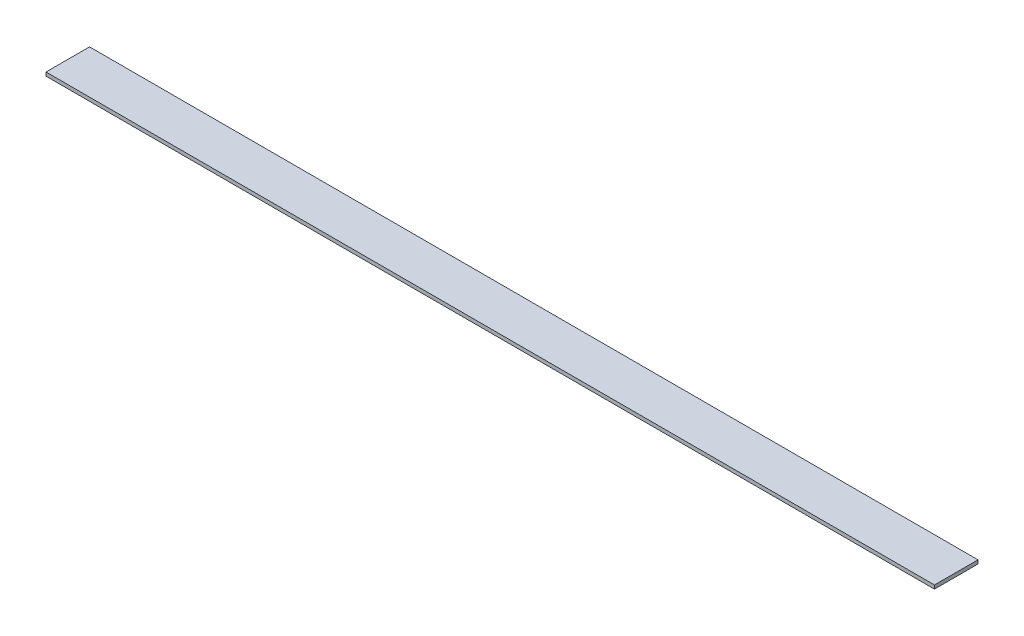
SolidWorks part; units mm, degrees
ref_plane "Front Plane" through (0, 0, 0) normal (0, 0, 1) x (1, 0, 0)
ref_plane "Top Plane" through (0, 0, 0) normal (0, 1, 0) x (1, 0, 0)
ref_plane "Right Plane" through (0, 0, 0) normal (1, 0, 0) x (0, 0, -1)
sketch "Sketch1" plane through (0, 0, 0) normal (0, 1, 0) x (1, 0, 0)
  line L1 (465, 277.5) -> (-465, 277.5)
  line L2 (465, 277.5) -> (465, -277.5)
  line L3 (465, -277.5) -> (-465, -277.5)
  line L4 (-465, 277.5) -> (-465, -277.5)
  line L5 (465, 277.5) -> (-465, -277.5) construction
  line L6 (465, -277.5) -> (-465, 277.5) construction
  line L7 (388.8, 239.4) -> (-388.8, 239.4)
  line L8 (388.8, 239.4) -> (388.8, -239.4)
  line L9 (388.8, -239.4) -> (-388.8, -239.4)
  line L10 (-388.8, 239.4) -> (-388.8, -239.4)
  line L11 (388.8, 239.4) -> (-388.8, -239.4) construction
  line L12 (388.8, -239.4) -> (-388.8, 239.4) construction
  point P0 (0, 0)
  point P6 (0, 0)
  dimension "D1" = 76.2
  dimension "D2" = 555
  dimension "D3" = 38.1
  dimension "D4" = 930
extrude "Boss-Extrude2" add sketch "Sketch1" along normal blind 3.175
sketch "Sketch2" plane through (0, 3.175, 0) normal (0, 1, 0) x (1, 0, 0)
  line L16 (-465, -277.5) -> (465, -277.5) construction
  line L17 (-465, 277.5) -> (-388.8, 277.5)
  line L18 (-465, 277.5) -> (-465, -277.5)
  line L19 (-465, -277.5) -> (-414.2, -277.5)
  line L20 (-388.8, 277.5) -> (-388.8, -239.4)
  line L21 (-388.8, -239.4) -> (388.8, -239.4) construction
  line L22 (465, 277.5) -> (388.8, 277.5)
  line L23 (465, 277.5) -> (465, -277.5)
  line L24 (465, -277.5) -> (414.2, -277.5)
  line L25 (388.8, 277.5) -> (388.8, -239.4)
  line L26 (-388.8, -239.4) -> (388.8, -239.4)
  line L28 (-414.2, -277.5) -> (414.2, -277.5)
  line L32 (-388.8, 239.4) -> (-388.8, -239.4) construction
  line L33 (388.8, -239.4) -> (388.8, 239.4) construction
extrude "Cut-Extrude1" cut sketch "Sketch2" against normal through all both and the other way through all
